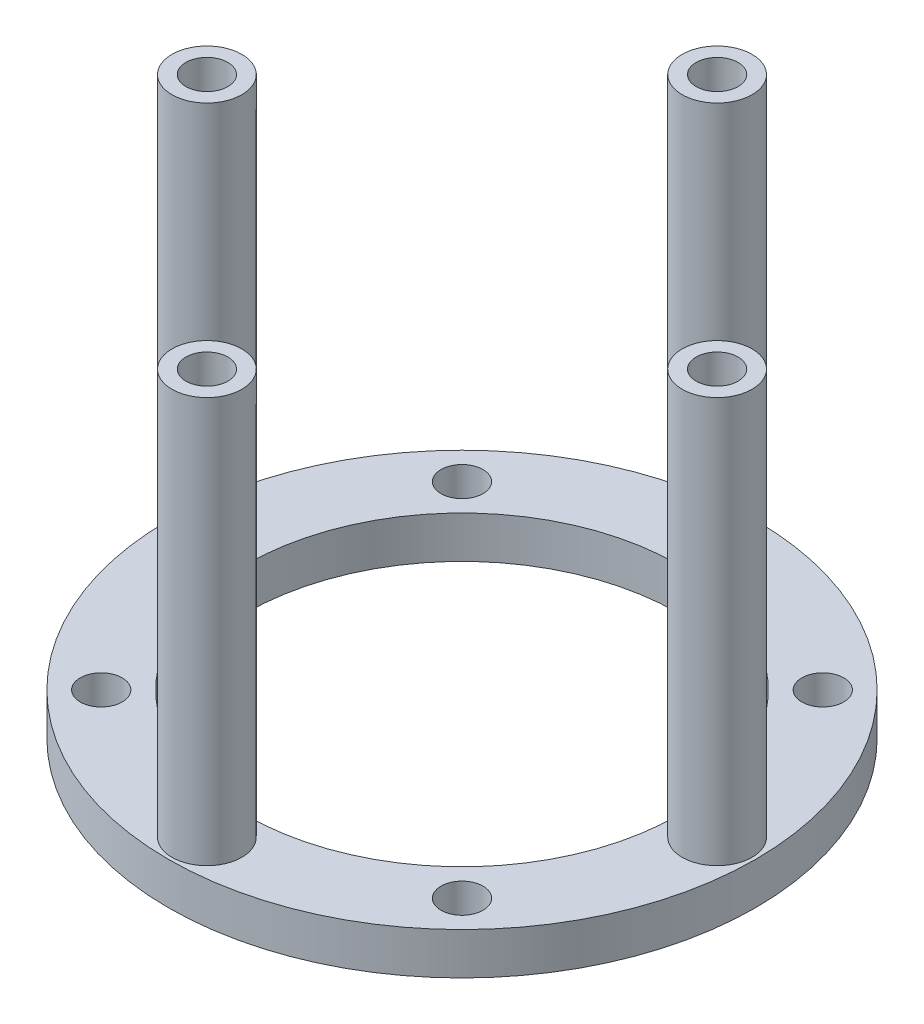
SolidWorks part; units mm, degrees
ref_plane "Front Plane" through (0, 0, 0) normal (0, 0, 1) x (1, 0, 0)
ref_plane "Top Plane" through (0, 0, 0) normal (0, 1, 0) x (1, 0, 0)
ref_plane "Right Plane" through (0, 0, 0) normal (1, 0, 0) x (0, 0, -1)
sketch "Sketch1" plane through (0, 0, 0) normal (0, 1, 0) x (1, 0, 0)
  circle A0 centre (0, 0) radius 21
  circle A1 centre (0, 0) radius 15.5
  circle A2 centre (0, 18.25) radius 1.5
  circle A3 centre (12.9047, 12.9047) radius 1.5
  circle A4 centre (18.25, 0) radius 1.5
  circle A5 centre (12.9047, -12.9047) radius 1.5
  circle A6 centre (0, -18.25) radius 1.5
  circle A7 centre (-12.9047, -12.9047) radius 1.5
  circle A8 centre (-18.25, 0) radius 1.5
  circle A9 centre (-12.9047, 12.9047) radius 1.5
  dimension "D1" = 42
  dimension "D2" = 31
  dimension "D3" = 3
  dimension "D4" = 18.25
  dimension "D5" = 8
extrude "Boss-Extrude1" add sketch "Sketch1" along normal blind 3
sketch "Sketch2" plane through (0, 3, 0) normal (0, 1, 0) x (1, 0, 0)
  circle A0 centre (0, 18.25) radius 2.5
  circle A1 centre (18.25, 0) radius 2.5
  circle A2 centre (0, -18.25) radius 2.5
  circle A3 centre (-18.25, 0) radius 2.5
  dimension "D1" = 5
  dimension "D2" = 4
extrude "Boss-Extrude2" add sketch "Sketch2" along normal blind 29
sketch "Sketch3" plane through (0, 32, 0) normal (0, 1, 0) x (1, 0, 0)
  circle A1 centre (18.25, 0) radius 1.5
  circle A2 centre (0, 18.25) radius 1.5
  circle A3 centre (0, 18.25) radius 1.5
  circle A4 centre (0, -18.25) radius 1.5
  circle A5 centre (-18.25, 0) radius 1.5
  dimension "D2" = 4
  dimension "D1" = 1
extrude "Cut-Extrude1" cut sketch "Sketch3" against normal blind 5
